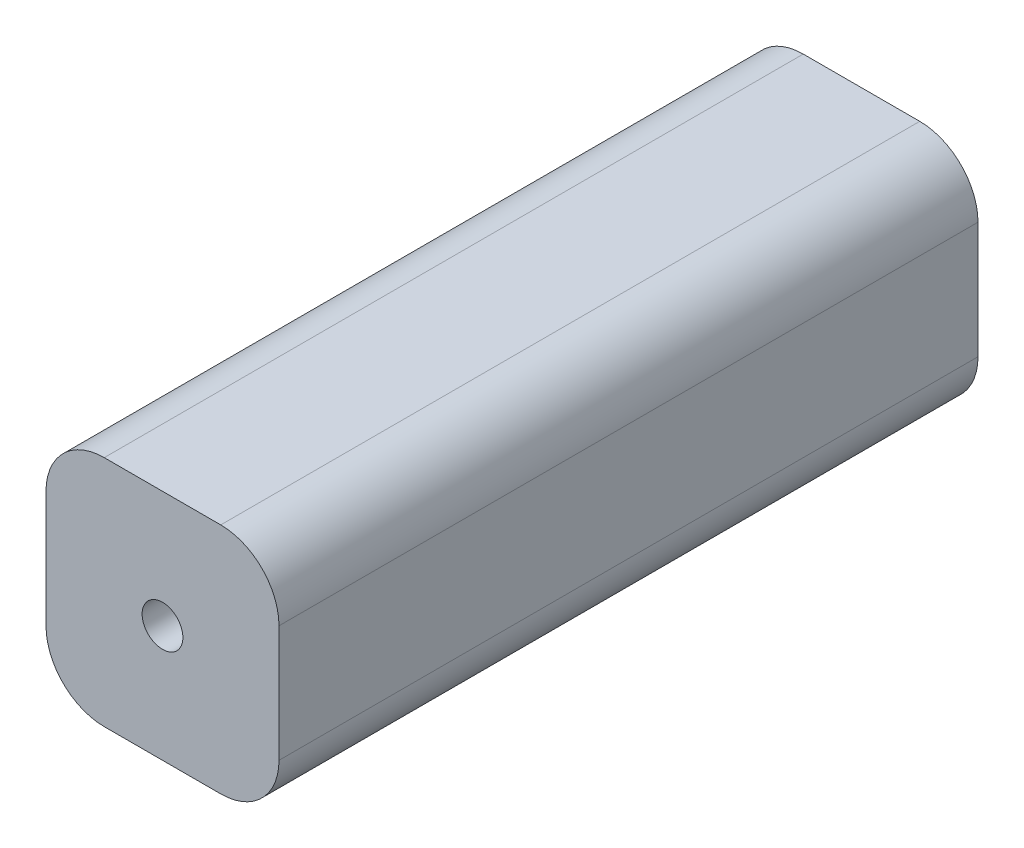
SolidWorks part; units mm, degrees
ref_plane "Plan de face" through (0, 0, 0) normal (0, 0, 1) x (1, 0, 0)
ref_plane "Plan de dessus" through (0, 0, 0) normal (0, 1, 0) x (1, 0, 0)
ref_plane "Plan de droite" through (0, 0, 0) normal (1, 0, 0) x (0, 0, -1)
sketch "Esquisse1" plane through (0, 0, 0) normal (0, 0, 1) x (1, 0, 0)
  line L1 (0, 0) -> (-20, 0)
  line L2 (0, 0) -> (0, 20)
  line L3 (0, 20) -> (-20, 20)
  line L4 (-20, 0) -> (-20, 20)
  dimension "D1" = 20
extrude "Boss.-Extru.1" add sketch "Esquisse1" along normal blind 60
sketch "Esquisse2" plane through (0, 0, 60) normal (0, 0, 1) x (1, 0, 0)
  line L0 (0, 20) -> (-20, 20) construction
  line L1 (0, 0) -> (0, 20) construction
  circle A0 centre (-10, 10) radius 1.75
  point P5 (-10, 20)
  point P8 (0, 10)
  dimension "D1" = 3.5
extrude "Enlèv. mat.-Extru.1" cut sketch "Esquisse2" against normal blind 15
sketch "Esquisse3" plane through (0, 0, 0) normal (0, 0, -1) x (-1, 0, 0)
  circle A1 centre (10, 10) radius 1.75 construction
  circle A2 centre (10, 10) radius 1.75
extrude "Enlèv. mat.-Extru.2" cut sketch "Esquisse3" against normal blind 15
fillet "Congé1" radius 5 4 edges at (-20, 0, 30) (0, 0, 30) (0, 20, 30) (-20, 20, 30)
